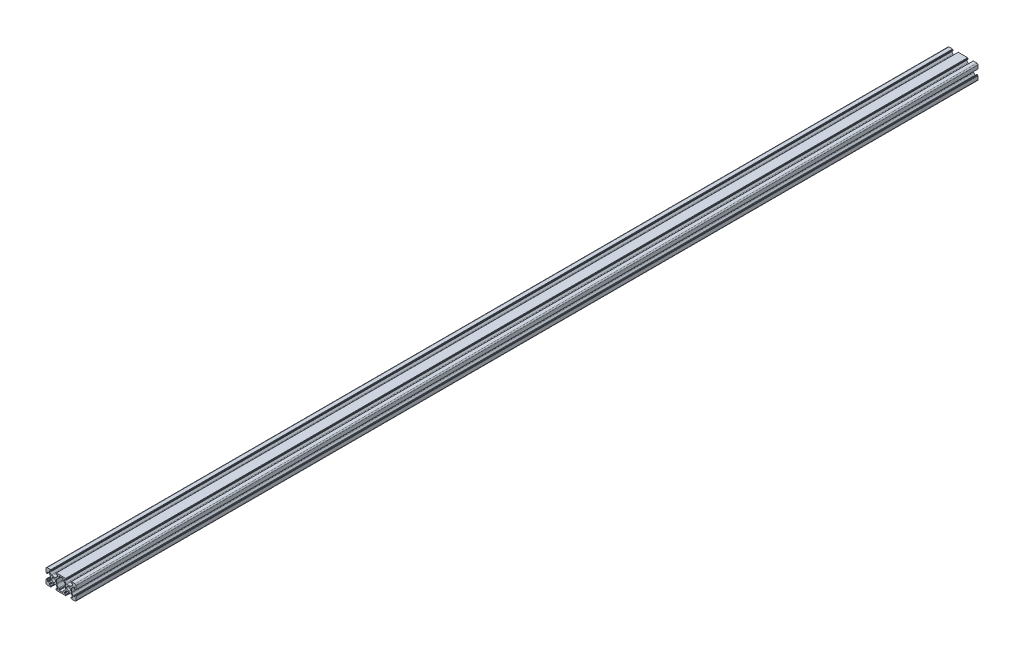
SolidWorks part; units mm, degrees
material "6063-O"
ref_plane "Front Plane" through (0, 0, 0) normal (0, 0, 1) x (1, 0, 0)
ref_plane "Top Plane" through (0, 0, 0) normal (0, 1, 0) x (1, 0, 0)
ref_plane "Right Plane" through (0, 0, 0) normal (1, 0, 0) x (0, 0, -1)
sketch "Sketch1" plane through (0, 0, 0) normal (0, 0, 1) x (1, 0, 0)
  line L0 (1.5, 0) -> (6.2, 0)
  line L1 (40, 1.5) -> (40, 6.2)
  line L2 (38.5, 20) -> (33.8, 20)
  line L3 (0, 18.5) -> (0, 13.8)
  line L4 (17.6, 1.8) -> (22.4, 1.8)
  line L5 (32.218, 13.9) -> (27.782, 13.9)
  line L6 (26.1, 12.218) -> (26.1, 7.782)
  line L7 (17.6, 18.2) -> (22.4, 18.2)
  line L8 (12.218, 13.9) -> (7.9864, 13.9)
  line L9 (6.1, 12.218) -> (6.1, 7.782)
  line L10 (7.782, 6.1) -> (12.218, 6.1)
  line L11 (13.9, 7.782) -> (13.9, 12.218)
  line L12 (27.782, 6.1) -> (32.218, 6.1)
  line L13 (33.9, 7.782) -> (33.9, 12.218)
  line L14 (26.7213, 14.3393) -> (24.9393, 16.1213)
  line L15 (33.2787, 14.3393) -> (35.0607, 16.1213)
  line L16 (34.3393, 13.2787) -> (36.1213, 15.0607)
  line L17 (25.6607, 6.7213) -> (23.1393, 4.2)
  line L18 (15.2, 1.8) -> (13.4, 1.8)
  line L19 (26.7213, 5.6607) -> (24.9393, 3.8787)
  line L20 (24.8, 1.8) -> (26.6, 1.8)
  line L21 (15.3, 18.2) -> (13.1, 18.2)
  line L22 (13.2787, 14.3393) -> (15.1607, 16.2213)
  line L23 (14.3393, 13.2787) -> (16.8607, 15.8)
  line L24 (5.6607, 6.7213) -> (3.8787, 4.9393)
  line L25 (6.7213, 5.6607) -> (4.9393, 3.8787)
  line L26 (6.897, 14.3689) -> (4.9106, 16.4674)
  line L27 (5.6607, 13.2787) -> (3.8787, 15.0607)
  line L28 (14.3393, 6.7213) -> (16.8607, 4.2)
  line L29 (13.2787, 5.6607) -> (15.0607, 3.8787)
  line L30 (24.8, 18.2) -> (26.6, 18.2)
  line L31 (25.6607, 13.2787) -> (23.1393, 15.8)
  line L32 (34.3393, 6.7213) -> (36.1213, 4.9393)
  line L33 (33.2787, 5.6607) -> (35.0607, 3.8787)
  line L34 (1.8, 15.2) -> (1.8, 13.4)
  line L35 (24.5, 2.1) -> (24.5, 2.818)
  line L36 (4.5, 2.1) -> (4.5, 2.818)
  line L37 (2.818, 4.5) -> (2.1, 4.5)
  line L38 (4.5, 17.9) -> (4.5, 17.4986)
  line L39 (2.818, 15.5) -> (2.1, 15.5)
  line L40 (15.6, 17.9) -> (15.6, 17.282)
  line L41 (15.5, 2.818) -> (15.5, 2.1)
  line L42 (38.2, 15.2) -> (38.2, 13.4)
  line L43 (35.5, 2.818) -> (35.5, 2.1)
  line L44 (37.182, 4.5) -> (37.9, 4.5)
  line L45 (35.5, 17.182) -> (35.5, 17.9)
  line L46 (37.182, 15.5) -> (37.9, 15.5)
  line L47 (17.3, 2.1) -> (17.3, 3.1393)
  line L48 (22.7, 2.1) -> (22.7, 3.1393)
  line L49 (17.3, 17.9) -> (17.3, 16.8607)
  line L50 (22.7, 17.9) -> (22.7, 16.8607)
  line L51 (24.5, 17.9) -> (24.5, 17.182)
  line L52 (6.9, 19.3) -> (6.9, 18.2)
  line L53 (13.1, 19.3) -> (13.1, 18.2)
  line L54 (6.9, 1.5) -> (6.9, 0.7)
  line L55 (13.1, 1.5) -> (13.1, 0.7)
  line L56 (13.8, 0) -> (26.2, 0)
  line L57 (6.6, 1.8) -> (4.8, 1.8)
  line L58 (6.9, 18.2) -> (4.8, 18.2)
  line L59 (6.2, 20) -> (1.5, 20)
  line L60 (39.3, 6.9) -> (38.5, 6.9)
  line L61 (39.3, 13.1) -> (38.5, 13.1)
  line L62 (1.5, 13.1) -> (0.7, 13.1)
  line L63 (1.5, 6.9) -> (0.7, 6.9)
  line L64 (0, 6.2) -> (0, 1.5)
  line L65 (1.8, 6.6) -> (1.8, 4.8)
  line L66 (38.2, 6.6) -> (38.2, 4.8)
  line L67 (40, 13.8) -> (40, 18.5)
  line L68 (33.1, 19.3) -> (33.1, 18.5)
  line L69 (26.9, 19.3) -> (26.9, 18.5)
  line L70 (26.9, 1.5) -> (26.9, 0.7)
  line L71 (33.1, 1.5) -> (33.1, 0.7)
  line L72 (33.8, 0) -> (38.5, 0)
  line L73 (33.4, 1.8) -> (35.2, 1.8)
  line L74 (26.2, 20) -> (13.8, 20)
  line L75 (33.4, 18.2) -> (35.2, 18.2)
  line L76 (6.7, 0.5) -> (6.6, 0.5)
  line L77 (6.4, 0.3) -> (6.4, 0.2)
  line L78 (13.3, 0.5) -> (13.4, 0.5)
  line L79 (13.6, 0.3) -> (13.6, 0.2)
  line L80 (26.7, 0.5) -> (26.6, 0.5)
  line L81 (26.4, 0.3) -> (26.4, 0.2)
  line L82 (33.3, 0.5) -> (33.4, 0.5)
  line L83 (33.6, 0.3) -> (33.6, 0.2)
  line L85 (6.4, 19.8) -> (6.4, 19.7)
  line L86 (6.6, 19.5) -> (6.7, 19.5)
  line L87 (13.6, 19.8) -> (13.6, 19.7)
  line L88 (13.4, 19.5) -> (13.3, 19.5)
  line L89 (26.4, 19.8) -> (26.4, 19.7)
  line L90 (26.6, 19.5) -> (26.7, 19.5)
  line L91 (33.6, 19.8) -> (33.6, 19.7)
  line L92 (33.4, 19.5) -> (33.3, 19.5)
  line L93 (0.5, 13.3) -> (0.5, 13.4)
  line L94 (0.3, 13.6) -> (0.2, 13.6)
  line L95 (0.5, 6.7) -> (0.5, 6.6)
  line L96 (0.3, 6.4) -> (0.2, 6.4)
  line L97 (39.5, 13.3) -> (39.5, 13.4)
  line L98 (39.7, 13.6) -> (39.8, 13.6)
  line L99 (39.5, 6.7) -> (39.5, 6.6)
  line L100 (39.7, 6.4) -> (39.8, 6.4)
  circle A0 centre (10, 10) radius 2.5
  circle A1 centre (30, 10) radius 2.5
  arc A2 (38.5, 0) -> (40, 1.5) centre (38.5, 1.5) ccw
  arc A3 (40, 18.5) -> (38.5, 20) centre (38.5, 18.5) ccw
  arc A4 (1.5, 0) -> (0, 1.5) centre (1.5, 1.5) cw
  arc A5 (1.5, 20) -> (0, 18.5) centre (1.5, 18.5) ccw
  arc A6 (26.7213, 5.6607) -> (27.782, 6.1) centre (27.782, 4.6) cw
  arc A7 (32.218, 6.1) -> (33.2787, 5.6607) centre (32.218, 4.6) cw
  arc A8 (33.9, 7.782) -> (34.3393, 6.7213) centre (35.4, 7.782) ccw
  arc A9 (33.2787, 14.3393) -> (32.218, 13.9) centre (32.218, 15.4) cw
  arc A10 (14.3393, 6.7213) -> (13.9, 7.782) centre (15.4, 7.782) cw
  arc A11 (14.3393, 13.2787) -> (13.9, 12.218) centre (15.4, 12.218) ccw
  arc A12 (25.6607, 6.7213) -> (26.1, 7.782) centre (24.6, 7.782) ccw
  arc A13 (26.1, 12.218) -> (25.6607, 13.2787) centre (24.6, 12.218) ccw
  arc A14 (27.782, 13.9) -> (26.7213, 14.3393) centre (27.782, 15.4) cw
  arc A15 (5.6607, 13.2787) -> (6.1, 12.218) centre (4.6, 12.218) cw
  arc A16 (5.6607, 6.7213) -> (6.1, 7.782) centre (4.6, 7.782) ccw
  arc A17 (13.2787, 5.6607) -> (12.218, 6.1) centre (12.218, 4.6) ccw
  arc A18 (6.7213, 5.6607) -> (7.782, 6.1) centre (7.782, 4.6) cw
  arc A19 (13.2787, 14.3393) -> (12.218, 13.9) centre (12.218, 15.4) cw
  arc A20 (6.897, 14.3689) -> (7.9864, 13.9) centre (7.9864, 15.4) ccw
  arc A21 (36.1213, 4.9393) -> (37.182, 4.5) centre (37.182, 6) ccw
  arc A22 (36.1213, 15.0607) -> (37.182, 15.5) centre (37.182, 14) cw
  arc A23 (35.0607, 16.1213) -> (35.5, 17.182) centre (34, 17.182) ccw
  arc A24 (24.5, 17.182) -> (24.9393, 16.1213) centre (26, 17.182) ccw
  arc A25 (22.7, 16.8607) -> (23.1393, 15.8) centre (24.2, 16.8607) ccw
  arc A26 (17.3, 16.8607) -> (16.8607, 15.8) centre (15.8, 16.8607) cw
  arc A27 (4.9106, 16.4674) -> (4.5, 17.4986) centre (6, 17.4986) cw
  arc A28 (15.6, 17.282) -> (15.1607, 16.2213) centre (14.1, 17.282) cw
  arc A29 (3.8787, 15.0607) -> (2.818, 15.5) centre (2.818, 14) ccw
  arc A30 (3.8787, 4.9393) -> (2.818, 4.5) centre (2.818, 6) cw
  arc A31 (4.9393, 3.8787) -> (4.5, 2.818) centre (6, 2.818) ccw
  arc A32 (35.0607, 3.8787) -> (35.5, 2.818) centre (34, 2.818) cw
  arc A33 (24.9393, 3.8787) -> (24.5, 2.818) centre (26, 2.818) ccw
  arc A34 (22.7, 3.1393) -> (23.1393, 4.2) centre (24.2, 3.1393) cw
  arc A35 (17.3, 3.1393) -> (16.8607, 4.2) centre (15.8, 3.1393) ccw
  arc A36 (15.5, 2.818) -> (15.0607, 3.8787) centre (14, 2.818) ccw
  arc A37 (1.8, 6.6) -> (1.5, 6.9) centre (1.5, 6.6) ccw
  arc A38 (1.8, 13.4) -> (1.5, 13.1) centre (1.5, 13.4) cw
  arc A39 (17.6, 18.2) -> (17.3, 17.9) centre (17.6, 17.9) ccw
  arc A40 (22.4, 1.8) -> (22.7, 2.1) centre (22.4, 2.1) ccw
  arc A41 (17.6, 1.8) -> (17.3, 2.1) centre (17.6, 2.1) cw
  arc A42 (15.2, 1.8) -> (15.5, 2.1) centre (15.2, 2.1) ccw
  arc A43 (6.6, 1.8) -> (6.9, 1.5) centre (6.6, 1.5) cw
  arc A44 (13.4, 1.8) -> (13.1, 1.5) centre (13.4, 1.5) ccw
  arc A45 (24.8, 1.8) -> (24.5, 2.1) centre (24.8, 2.1) cw
  arc A46 (35.2, 1.8) -> (35.5, 2.1) centre (35.2, 2.1) ccw
  arc A47 (26.6, 1.8) -> (26.9, 1.5) centre (26.6, 1.5) cw
  arc A48 (33.4, 1.8) -> (33.1, 1.5) centre (33.4, 1.5) ccw
  arc A49 (26.9, 18.5) -> (26.6, 18.2) centre (26.6, 18.5) cw
  arc A50 (33.1, 18.5) -> (33.4, 18.2) centre (33.4, 18.5) ccw
  arc A51 (37.9, 4.5) -> (38.2, 4.8) centre (37.9, 4.8) ccw
  arc A52 (38.5, 13.1) -> (38.2, 13.4) centre (38.5, 13.4) cw
  arc A53 (38.5, 6.9) -> (38.2, 6.6) centre (38.5, 6.6) ccw
  arc A54 (38.2, 15.2) -> (37.9, 15.5) centre (37.9, 15.2) ccw
  arc A55 (35.2, 18.2) -> (35.5, 17.9) centre (35.2, 17.9) cw
  arc A56 (24.8, 18.2) -> (24.5, 17.9) centre (24.8, 17.9) ccw
  arc A57 (22.4, 18.2) -> (22.7, 17.9) centre (22.4, 17.9) cw
  arc A58 (15.3, 18.2) -> (15.6, 17.9) centre (15.3, 17.9) cw
  arc A59 (4.5, 17.9) -> (4.8, 18.2) centre (4.8, 17.9) cw
  arc A60 (1.8, 15.2) -> (2.1, 15.5) centre (2.1, 15.2) cw
  arc A61 (1.8, 4.8) -> (2.1, 4.5) centre (2.1, 4.8) ccw
  arc A62 (4.5, 2.1) -> (4.8, 1.8) centre (4.8, 2.1) ccw
  arc A63 (34.3393, 13.2787) -> (33.9, 12.218) centre (35.4, 12.218) ccw
  arc A64 (6.4, 0.2) -> (6.2, 0) centre (6.2, 0.2) cw
  arc A65 (6.6, 0.5) -> (6.4, 0.3) centre (6.6, 0.3) ccw
  arc A66 (6.7, 0.5) -> (6.9, 0.7) centre (6.7, 0.7) ccw
  arc A67 (13.6, 0.2) -> (13.8, 0) centre (13.8, 0.2) ccw
  arc A68 (13.4, 0.5) -> (13.6, 0.3) centre (13.4, 0.3) cw
  arc A69 (13.3, 0.5) -> (13.1, 0.7) centre (13.3, 0.7) cw
  arc A70 (26.4, 0.2) -> (26.2, 0) centre (26.2, 0.2) cw
  arc A71 (26.6, 0.5) -> (26.4, 0.3) centre (26.6, 0.3) ccw
  arc A72 (26.7, 0.5) -> (26.9, 0.7) centre (26.7, 0.7) ccw
  arc A73 (33.6, 0.2) -> (33.8, 0) centre (33.8, 0.2) ccw
  arc A74 (33.4, 0.5) -> (33.6, 0.3) centre (33.4, 0.3) cw
  arc A75 (33.3, 0.5) -> (33.1, 0.7) centre (33.3, 0.7) cw
  arc A76 (39.8, 6.4) -> (40, 6.2) centre (39.8, 6.2) cw
  arc A77 (39.5, 6.6) -> (39.7, 6.4) centre (39.7, 6.6) ccw
  arc A78 (39.5, 6.7) -> (39.3, 6.9) centre (39.3, 6.7) ccw
  arc A79 (39.5, 13.3) -> (39.3, 13.1) centre (39.3, 13.3) cw
  arc A80 (39.5, 13.4) -> (39.7, 13.6) centre (39.7, 13.4) cw
  arc A81 (39.8, 13.6) -> (40, 13.8) centre (39.8, 13.8) ccw
  arc A82 (33.3, 19.5) -> (33.1, 19.3) centre (33.3, 19.3) ccw
  arc A83 (33.6, 19.7) -> (33.4, 19.5) centre (33.4, 19.7) cw
  arc A84 (33.6, 19.8) -> (33.8, 20) centre (33.8, 19.8) cw
  arc A85 (26.7, 19.5) -> (26.9, 19.3) centre (26.7, 19.3) cw
  arc A86 (26.4, 19.7) -> (26.6, 19.5) centre (26.6, 19.7) ccw
  arc A87 (26.4, 19.8) -> (26.2, 20) centre (26.2, 19.8) ccw
  arc A88 (0.2, 6.4) -> (0, 6.2) centre (0.2, 6.2) ccw
  arc A89 (0.5, 6.6) -> (0.3, 6.4) centre (0.3, 6.6) cw
  arc A90 (0.5, 6.7) -> (0.7, 6.9) centre (0.7, 6.7) cw
  arc A91 (13.3, 19.5) -> (13.1, 19.3) centre (13.3, 19.3) ccw
  arc A92 (13.6, 19.7) -> (13.4, 19.5) centre (13.4, 19.7) cw
  arc A93 (13.6, 19.8) -> (13.8, 20) centre (13.8, 19.8) cw
  arc A94 (6.2, 20) -> (6.4, 19.8) centre (6.2, 19.8) cw
  arc A95 (6.7, 19.5) -> (6.9, 19.3) centre (6.7, 19.3) cw
  arc A96 (6.4, 19.7) -> (6.6, 19.5) centre (6.6, 19.7) ccw
  arc A97 (0.5, 13.3) -> (0.7, 13.1) centre (0.7, 13.3) ccw
  arc A98 (0.2, 13.6) -> (0, 13.8) centre (0.2, 13.8) cw
  arc A99 (0.5, 13.4) -> (0.3, 13.6) centre (0.3, 13.4) ccw
  point P87 (0, 0)
  point P178 (1.8, 6.9)
  point P181 (1.8, 13.1)
  point P186 (22.7, 1.8)
  point P193 (6.9, 1.8)
  point P204 (33.1, 1.8)
  point P209 (33.1, 18.2)
  point P216 (38.2, 6.9)
  point P243 (6.9, 0.5)
  point P248 (13.6, 0.5)
  point P257 (26.9, 0.5)
extrude "Boss-Extrude2" add sketch "Sketch1" along normal blind 1200 contours A57 L7 A39 L49 A26 L23 A11 L11 A10 L28 A35 L47 A41 L4 A40 L48 A34 L17 A12 L6 A13 L31 A25 L50 | A0 | A1 | L59 A5 L3 A98 L94 A99 L93 A97 L62 A38 L34 A60 L39 A29 L27 A15 L9 A16 L24 A30 L37 A61 L65 A37 L63 A90 L95 A89 L96 A88 L64 A4 L0 A64 L77 A65 L76 A66 L54 A43 L57 A62 L36 A31 L25 A18 L10 A17 L29 A36 L41 A42 L18 A44 L55 A69 L78 A68 L79 A67 L56 A70 L81 A71 L80 A72 L70 A47 L20 A45 L35 A33 L19 A6 L12 A7 L33 A32 L43 A46 L73 A48 L71 A75 L82 A74 L83 A73 L72 A2 L1 A76 L100 A77 L99 A78 L60 A53 L66 A51 L44 A21 L32 A8 L13 A63 L16 A22 L46 A54 L42 A52 L61 A79 L97 A80 L98 A81 L67 A3 L2 A84 L91 A83 L92 A82 L68 A50 L75 A55 L45 A23 L15 A9 L5 A14 L14 A24 L51 A56 L30 A49 L69 A85 L90 A86 L89 A87 L74 A93 L87 A92 L88 A91 L53 L21 A58 L40 A28 L22 A19 L8 A20 L26 A27 L38 A59 L58 L52 A95 L86 A96 L85 A94
